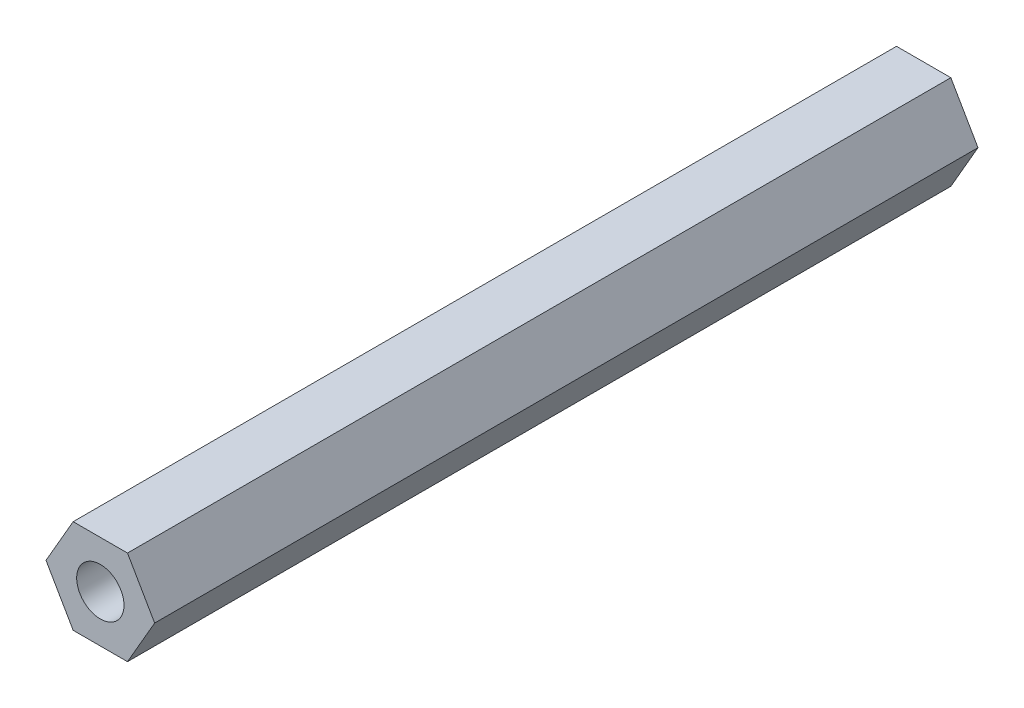
SolidWorks part; units mm, degrees
material "黄铜"
ref_plane "前视基准面" through (0, 0, 0) normal (0, 0, 1) x (1, 0, 0)
ref_plane "上视基准面" through (0, 0, 0) normal (0, 1, 0) x (1, 0, 0)
ref_plane "右视基准面" through (0, 0, 0) normal (1, 0, 0) x (0, 0, -1)
other "Configuration Table"
sketch "六角对边与轴向孔" plane through (0, 0, 0) normal (0, 0, 1) x (1, 0, 0)
  line L0 (4.6188, 0) -> (2.3094, 4)
  line L1 (2.3094, 4) -> (-2.3094, 4)
  line L2 (-2.3094, 4) -> (-4.6188, 0)
  line L3 (-4.6188, 0) -> (-2.3094, -4)
  line L4 (-2.3094, -4) -> (2.3094, -4)
  line L5 (2.3094, -4) -> (4.6188, 0)
extrude "隔柱高度_70mm" add sketch "六角对边与轴向孔" along normal blind 70
sketch "底端_M4内牙轮廓" plane through (0, 0, 0) normal (0, 0, -1) x (-1, 0, 0)
  circle A0 centre (0, 0) radius 2.01
extrude "底端_M4内牙" cut sketch "底端_M4内牙轮廓" against normal blind 10
sketch "顶端_M4内牙轮廓" plane through (0, 0, 70) normal (0, 0, 1) x (1, 0, 0)
  circle A0 centre (0, 0) radius 2.01
extrude "顶端_M4内牙" cut sketch "顶端_M4内牙轮廓" against normal blind 10
